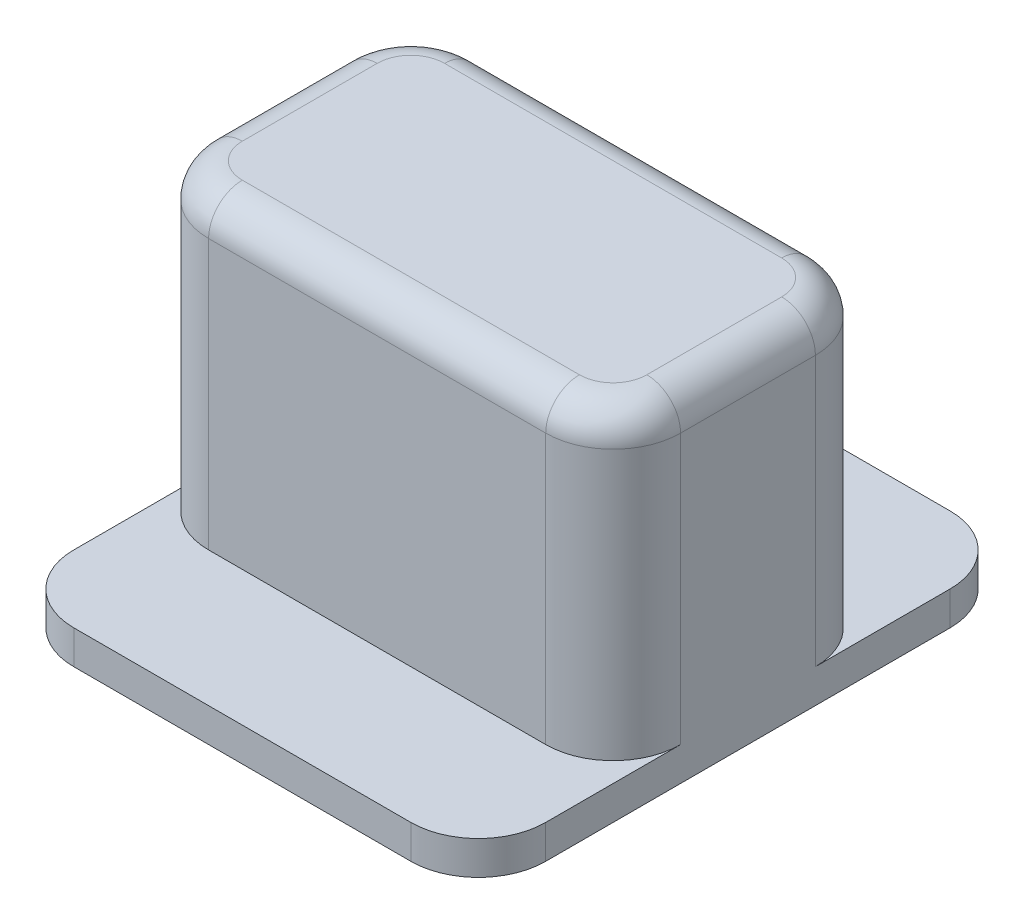
SolidWorks part; units mm, degrees
ref_plane "Front Plane" through (0, 0, 0) normal (0, 0, 1) x (1, 0, 0)
ref_plane "Top Plane" through (0, 0, 0) normal (0, 1, 0) x (1, 0, 0)
ref_plane "Right Plane" through (0, 0, 0) normal (1, 0, 0) x (0, 0, -1)
sketch "草图1" plane through (0, 0, 0) normal (0, 1, 0) x (1, 0, 0)
  line L4 (26.5529, 0.5) -> (33.5529, 0.5)
  line L5 (33.5529, 0.5) -> (33.5529, 8.5)
  line L6 (33.5529, 8.5) -> (26.5529, 8.5)
  line L7 (26.5529, 8.5) -> (26.5529, 0.5)
extrude "凸台-拉伸1" add sketch "草图1" along normal blind 1
sketch "草图2" plane through (0, 1, 0) normal (0, 1, 0) x (1, 0, 0)
  line L0 (26.5529, 4.5) -> (26.5529, 6.5)
  line L1 (26.5529, 8.5) -> (26.5529, 0.5) construction
  line L2 (26.5529, 6.5) -> (33.5529, 6.5)
  line L3 (33.5529, 0.5) -> (33.5529, 8.5) construction
  line L4 (33.5529, 6.5) -> (33.5529, 2.5)
  line L5 (33.5529, 2.5) -> (26.5529, 2.5)
  line L6 (26.5529, 2.5) -> (26.5529, 4.5)
extrude "凸台-拉伸2" add sketch "草图2" along normal blind 4.5
fillet "圆角1" radius 1 8 edges at (26.5529, 0.5, -8.5) (26.5529, 3.25, -6.5) (26.5529, 3.25, -2.5) (33.5529, 3.25, -2.5) (33.5529, 3.25, -6.5) (33.5529, 0.5, -8.5) (26.5529, 0.5, -0.5) (33.5529, 0.5, -0.5)
fillet "圆角2" radius 0.5 8 edges at (33.26, 5.5, -6.2071) (33.5529, 5.5, -4.5) (33.26, 5.5, -2.7929) (30.0529, 5.5, -2.5) (26.8458, 5.5, -2.7929) (26.5529, 5.5, -4.5) (26.8458, 5.5, -6.2071) (30.0529, 5.5, -6.5)
sketch "草图3" plane through (0, 0, 0) normal (0, -1, 0) x (1, 0, 0)
  line L4 (26.5529, -1.5) -> (26.5529, -7.5)
  line L5 (27.5529, -8.5) -> (32.5529, -8.5)
  line L6 (33.5529, -7.5) -> (33.5529, -1.5)
  line L7 (32.5529, -0.5) -> (27.5529, -0.5)
  line L8 (26.5529, -1.5) -> (26.5529, -7.5)
  line L9 (27.5529, -8.5) -> (32.5529, -8.5)
  line L10 (33.5529, -7.5) -> (33.5529, -1.5)
  line L11 (32.5529, -0.5) -> (27.5529, -0.5)
  arc A4 (26.5529, -7.5) -> (27.5529, -8.5) centre (27.5529, -7.5) ccw
  arc A5 (32.5529, -8.5) -> (33.5529, -7.5) centre (32.5529, -7.5) ccw
  arc A6 (33.5529, -1.5) -> (32.5529, -0.5) centre (32.5529, -1.5) ccw
  arc A7 (27.5529, -0.5) -> (26.5529, -1.5) centre (27.5529, -1.5) ccw
  arc A8 (26.5529, -7.5) -> (27.5529, -8.5) centre (27.5529, -7.5) ccw
  arc A9 (32.5529, -8.5) -> (33.5529, -7.5) centre (32.5529, -7.5) ccw
  arc A10 (33.5529, -1.5) -> (32.5529, -0.5) centre (32.5529, -1.5) ccw
  arc A11 (27.5529, -0.5) -> (26.5529, -1.5) centre (27.5529, -1.5) ccw
  dimension "D1" = 0
extrude "切除-拉伸1" cut sketch "草图3" against normal blind 0.5
